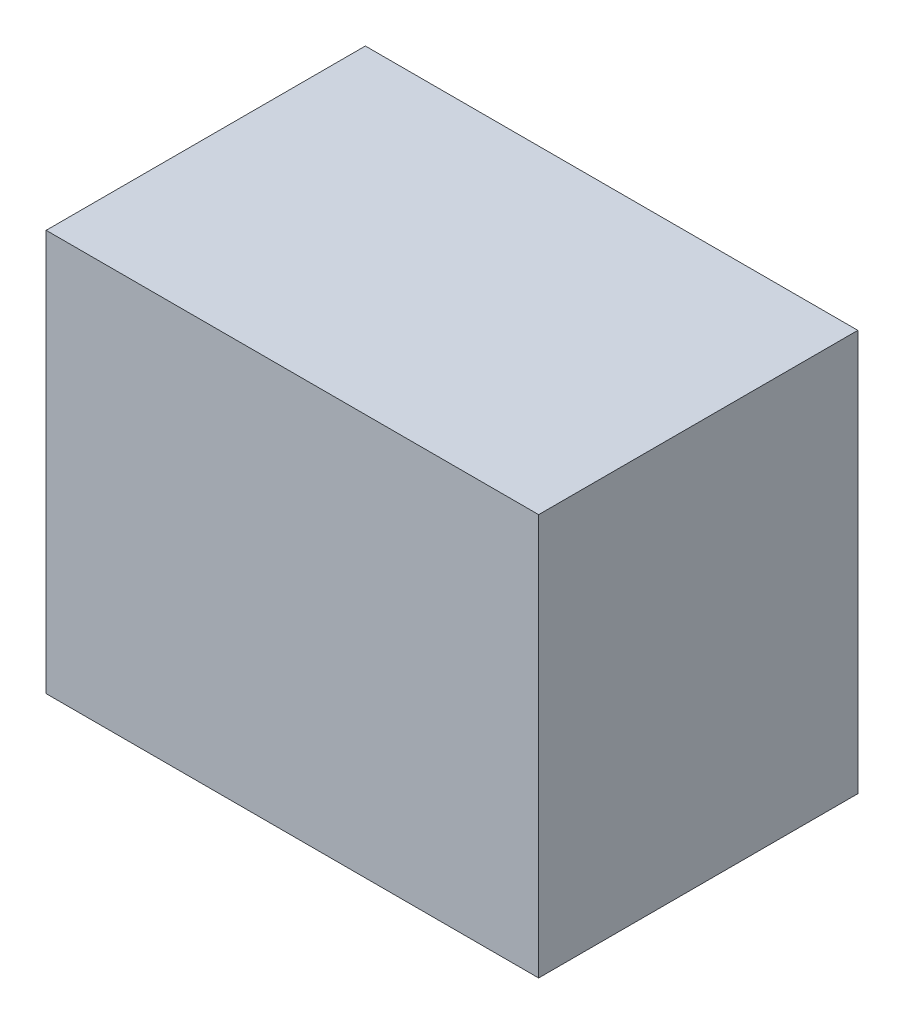
SolidWorks part; units mm, degrees
ref_plane "Płaszczyzna przednia" through (0, 0, 0) normal (0, 0, 1) x (1, 0, 0)
ref_plane "Płaszczyzna górna" through (0, 0, 0) normal (0, 1, 0) x (1, 0, 0)
ref_plane "Płaszczyzna prawa" through (0, 0, 0) normal (1, 0, 0) x (0, 0, -1)
sketch "Szkic1" plane through (0, 0, 0) normal (0, 1, 0) x (1, 0, 0)
  line L1 (-135, 87.5) -> (135, 87.5)
  line L2 (-135, 87.5) -> (-135, -87.5)
  line L3 (-135, -87.5) -> (135, -87.5)
  line L4 (135, 87.5) -> (135, -87.5)
  line L5 (-135, 87.5) -> (135, -87.5) construction
  line L6 (-135, -87.5) -> (135, 87.5) construction
  point P0 (0, 0)
  dimension "D1" = 270
  dimension "D2" = 175
extrude "Dodanie-wyciągnięcie1" add sketch "Szkic1" along normal blind 220
